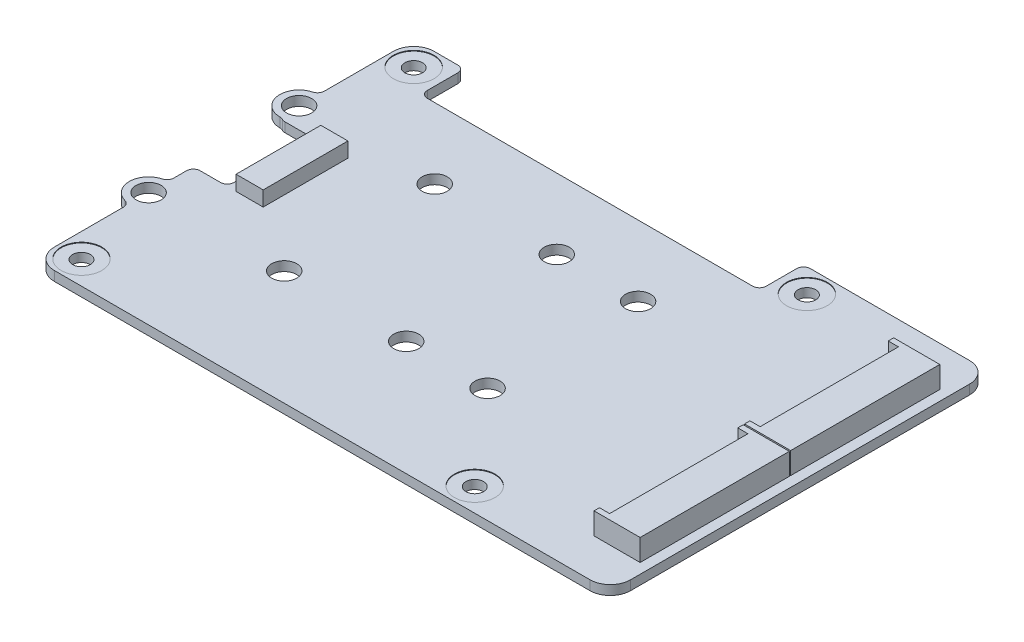
SolidWorks part; units mm, degrees
ref_plane "前视基准面" through (0, 0, 0) normal (0, 0, 1) x (1, 0, 0)
ref_plane "上视基准面" through (0, 0, 0) normal (0, 1, 0) x (1, 0, 0)
ref_plane "右视基准面" through (0, 0, 0) normal (1, 0, 0) x (0, 0, -1)
sketch "草图1" plane through (0, 0, 0) normal (0, 1, 0) x (1, 0, 0)
  line L1 (-42.5743, 23.4419) -> (42.4257, 23.4419)
  line L2 (-42.5743, 23.4419) -> (-42.5743, -32.5581)
  line L3 (-42.5743, -32.5581) -> (42.4257, -32.5581)
  line L4 (42.4257, 23.4419) -> (42.4257, -32.5581)
  dimension "D1" = 85
  dimension "D2" = 56
extrude "凸台-拉伸1" add sketch "草图1" along normal blind 1.4
fillet "圆角1" radius 3 4 edges at (42.4257, 0.7, -23.4419) (42.4257, 0.7, 32.5581) (-42.5743, 0.7, 32.5581) (-42.5743, 0.7, -23.4419)
sketch "草图2" plane through (0, 1.4, 0) normal (0, 1, 0) x (1, 0, 0)
  line L0 (39.4257, 23.4419) -> (-39.5743, 23.4419) construction
  line L1 (-42.5743, 20.4419) -> (-42.5743, -29.5581) construction
  line L2 (-39.5743, -32.5581) -> (39.4257, -32.5581) construction
  circle A0 centre (-39.0743, 19.9419) radius 1.3
  circle A1 centre (-39.0743, -29.0581) radius 1.3
  circle A2 centre (18.9257, -29.0581) radius 1.3
  circle A3 centre (18.9257, 19.9419) radius 1.3
  point P16 (0, 0)
  point P17 (0, 0)
  point P18 (0, 0)
  point P19 (0, 0)
  point P20 (0, 0)
  dimension "D1" = 2.6
  dimension "D2" = 3.5
  dimension "D3" = 3.5
  dimension "D4" = 3.5
  dimension "D5" = 58
extrude "切除-拉伸1" cut sketch "草图2" against normal blind 1.5
sketch "草图7" plane through (0, 1.4, 0) normal (0, 1, 0) x (1, 0, 0)
  circle A0 centre (-39.0743, 19.9419) radius 3
  circle A1 centre (18.9257, 19.9419) radius 3
  circle A2 centre (-39.0743, -29.0581) radius 3
  circle A3 centre (18.9257, -29.0581) radius 3
  dimension "D1" = 6
extrude "切除-拉伸4" cut sketch "草图7" against normal blind 0.1
sketch "草图3" plane through (0, 1.4, 0) normal (0, 1, 0) x (1, 0, 0)
  line L0 (-42.5743, 20.4419) -> (-42.5743, -29.5581) construction
  line L1 (-42.5743, 3.4419) -> (-37.5743, 3.4419)
  line L2 (-42.5743, 3.4419) -> (-42.5743, -9.0581)
  line L3 (-42.5743, -9.0581) -> (-37.5743, -9.0581)
  line L4 (-37.5743, 3.4419) -> (-37.5743, -9.0581)
  line L5 (39.4257, 23.4419) -> (-39.5743, 23.4419) construction
  line L6 (-39.5743, -32.5581) -> (39.4257, -32.5581) construction
  dimension "D1" = 20
  dimension "D2" = 23.5
  dimension "D3" = 5
extrude "切除-拉伸2" cut sketch "草图3" against normal blind 1.5
fillet "圆角2" radius 1 4 edges at (-42.5743, 0.7, 9.0581) (-37.5743, 0.7, 9.0581) (-37.5743, 0.7, -3.4419) (-42.5743, 0.7, -3.4419)
sketch "草图8" plane through (0, 1.4, 0) normal (0, 1, 0) x (1, 0, 0)
  line L0 (39.4257, 23.4419) -> (-39.5743, 23.4419) construction
  line L1 (-35.0743, 23.4419) -> (14.9257, 23.4419)
  line L2 (-35.0743, 23.4419) -> (-35.0743, 16.9419)
  line L3 (-35.0743, 16.9419) -> (14.9257, 16.9419)
  line L4 (14.9257, 23.4419) -> (14.9257, 16.9419)
  line L5 (-42.5743, 20.4419) -> (-42.5743, 4.4419) construction
  dimension "D1" = 50
  dimension "D2" = 7.5
  dimension "D3" = 6.5
extrude "切除-拉伸5" cut sketch "草图8" against normal through all
fillet "圆角3" radius 1 4 edges at (14.9257, 0.7, -16.9419) (14.9257, 0.7, -23.4419) (-35.0743, 0.7, -16.9419) (-35.0743, 0.7, -23.4419)
sketch "草图4" plane through (0, 1.4, 0) normal (0, 1, 0) x (1, 0, 0)
  line L0 (39.4257, 23.4419) -> (15.9257, 23.4419) construction
  line L1 (34.1257, 17.5419) -> (40.9257, 17.5419)
  line L2 (34.1257, 17.5419) -> (34.1257, -4.4581)
  line L3 (34.1257, -4.4581) -> (40.9257, -4.4581)
  line L4 (40.9257, 17.5419) -> (40.9257, -4.4581)
  line L5 (34.1257, -4.6581) -> (40.9257, -4.6581)
  line L6 (34.1257, -4.6581) -> (34.1257, -26.6581)
  line L7 (34.1257, -26.6581) -> (40.9257, -26.6581)
  line L8 (40.9257, -4.6581) -> (40.9257, -26.6581)
  line L9 (-39.5743, -32.5581) -> (39.4257, -32.5581) construction
  line L10 (42.4257, -29.5581) -> (42.4257, 20.4419) construction
  point P8 (0, 0)
  dimension "D1" = 22
  dimension "D2" = 6.8
  dimension "D3" = 5.9
  dimension "D4" = 5.9
  dimension "D5" = 1.5
extrude "凸台-拉伸2" add sketch "草图4" along normal blind 3.2
sketch "草图5" plane through (0, 4.6, 0) normal (0, 1, 0) x (1, 0, 0)
  line L0 (34.1257, 17.5419) -> (34.1257, -4.4581) construction
  line L1 (34.1257, 16.7419) -> (35.6257, 16.7419)
  line L2 (34.1257, 16.7419) -> (34.1257, -3.6581)
  line L3 (34.1257, -3.6581) -> (35.6257, -3.6581)
  line L4 (35.6257, 16.7419) -> (35.6257, -3.6581)
  line L5 (34.1257, -4.6581) -> (34.1257, -26.6581) construction
  line L6 (34.1257, -5.4581) -> (35.6257, -5.4581)
  line L7 (34.1257, -5.4581) -> (34.1257, -25.8581)
  line L8 (34.1257, -25.8581) -> (35.6257, -25.8581)
  line L9 (35.6257, -5.4581) -> (35.6257, -25.8581)
  line L10 (40.9257, 17.5419) -> (34.1257, 17.5419) construction
  line L11 (34.1257, -4.4581) -> (40.9257, -4.4581) construction
  line L12 (34.1257, -26.6581) -> (40.9257, -26.6581) construction
  point P19 (0, 0)
  dimension "D1" = 0.8
  dimension "D2" = 0.8
  dimension "D3" = 0.8
  dimension "D4" = 0.8
  dimension "D5" = 1.5
extrude "切除-拉伸3" cut sketch "草图5" against normal blind 1.8
sketch "草图6" plane through (0, 1.4, 0) normal (0, 1, 0) x (1, 0, 0)
  line L0 (-37.5743, -8.0581) -> (-37.5743, 2.4419) construction
  line L1 (-36.2743, 3.4419) -> (-32.2743, 3.4419)
  line L2 (-36.2743, 3.4419) -> (-36.2743, -9.0581)
  line L3 (-36.2743, -9.0581) -> (-32.2743, -9.0581)
  line L4 (-32.2743, 3.4419) -> (-32.2743, -9.0581)
  line L5 (-39.5743, -32.5581) -> (39.4257, -32.5581) construction
  dimension "D1" = 4
  dimension "D2" = 12.5
  dimension "D3" = 1.3
  dimension "D4" = 23.5
extrude "凸台-拉伸3" add sketch "草图6" along normal blind 2.2
sketch "草图10" plane through (0, 1.4, 0) normal (0, 1, 0) x (1, 0, 0)
  line L0 (-42.5743, 20.4419) -> (-42.5743, 4.4419) construction
  line L1 (-42.5743, -10.0581) -> (-42.5743, -29.5581) construction
  line L2 (-36.0743, 23.4419) -> (-39.5743, 23.4419) construction
  line L3 (-39.5743, -32.5581) -> (39.4257, -32.5581) construction
  circle A0 centre (-42.5743, 6.5419) radius 2.85
  circle A1 centre (-42.5743, -15.6581) radius 2.85
  point P6 (0, 0)
  point P7 (0, 0)
  point P10 (0, 0)
  point P13 (0, 0)
  dimension "D3" = 5.7
  dimension "D1" = 16.9
  dimension "D2" = 16.9
extrude "凸台-拉伸4" add sketch "草图10" against normal blind 1.4
sketch "草图9" plane through (0, 1.4, 0) normal (0, 1, 0) x (1, 0, 0)
  line L0 (37.4257, 31.1428) -> (37.4257, -39.8536) construction
  line L1 (-69.1635, 6.5419) -> (-53.1644, 6.5419) construction
  line L2 (7.4257, 44.4259) -> (7.4257, -44.0828) construction
  line L3 (-4.5743, 36.4008) -> (-4.5743, -42.3964) construction
  line L4 (-22.5743, 29.1899) -> (-22.5743, -39.5469) construction
  line L5 (-42.5743, 27.2708) -> (-42.5743, -38.9072) construction
  line L6 (-68.4488, -15.6581) -> (-55.4736, -15.6581) construction
  line L8 (34.1257, 16.7419) -> (34.1257, -3.6581) construction
  line L9 (34.1257, -4.6581) -> (34.1257, -26.6581) construction
  circle A0 centre (7.4257, 6.5419) radius 1.85
  circle A1 centre (-4.5743, 6.5419) radius 1.85
  circle A2 centre (-22.5743, 6.5419) radius 1.85
  circle A3 centre (-22.5743, -15.6581) radius 1.85
  circle A4 centre (-4.5743, -15.6581) radius 1.85
  circle A5 centre (7.4257, -15.6581) radius 1.85
  circle A6 centre (-42.5743, 6.5419) radius 1.85
  circle A7 centre (-42.5743, -15.6581) radius 1.85
  point P19 (34.1257, 6.5419)
  point P20 (34.1257, -15.6581)
  dimension "D6" = 3.7
  dimension "D1" = 30
  dimension "D2" = 3.5
  dimension "D3" = 42
  dimension "D4" = 60
  dimension "D5" = 80
extrude "切除-拉伸6" cut sketch "草图9" against normal through all
fillet "圆角4" radius 1 4 edges at (-42.5743, 0.7, -9.3919) (-42.2555, 0.7, -3.7098) (-42.5743, 0.7, 12.8081) (-42.5743, 0.7, 18.5081)
